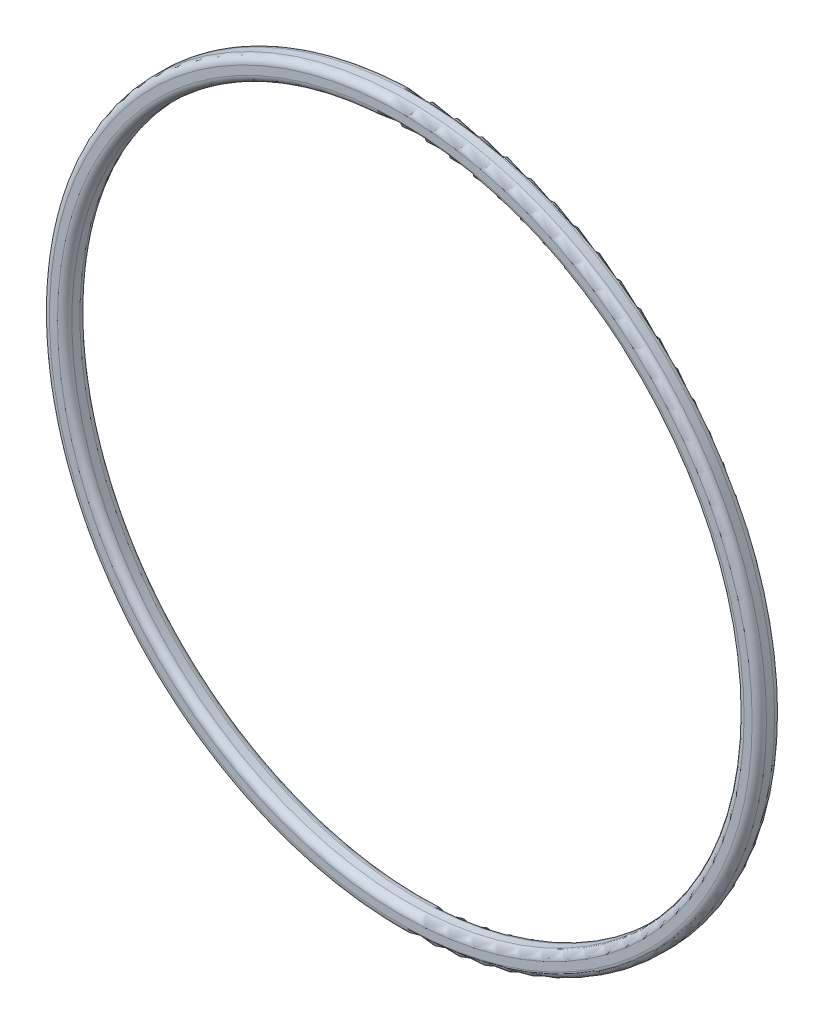
SolidWorks part; units mm, degrees
ref_plane "Front Plane" through (0, 0, 0) normal (0, 0, 1) x (1, 0, 0)
ref_plane "Top Plane" through (0, 0, 0) normal (0, 1, 0) x (1, 0, 0)
ref_plane "Right Plane" through (0, 0, 0) normal (1, 0, 0) x (0, 0, -1)
sketch "Sketch1" plane through (0, 0, 0) normal (0, 0, 1) x (1, 0, 0)
  circle A0 centre (0, 0) radius 23.8125
  circle A1 centre (0, 0) radius 25.4
  dimension "D1" = 47.625
  dimension "D2" = 50.8
extrude "Boss-Extrude1" add sketch "Sketch1" along normal blind 1.5875
fillet "Fillet1" radius 0.508 4 edges at (23.8125, 0, 1.5875) (23.8125, 0, 0) (25.4, 0, 0) (25.4, 0, 1.5875)
equation "\"D1@Sketch1\"=1+7/8"
